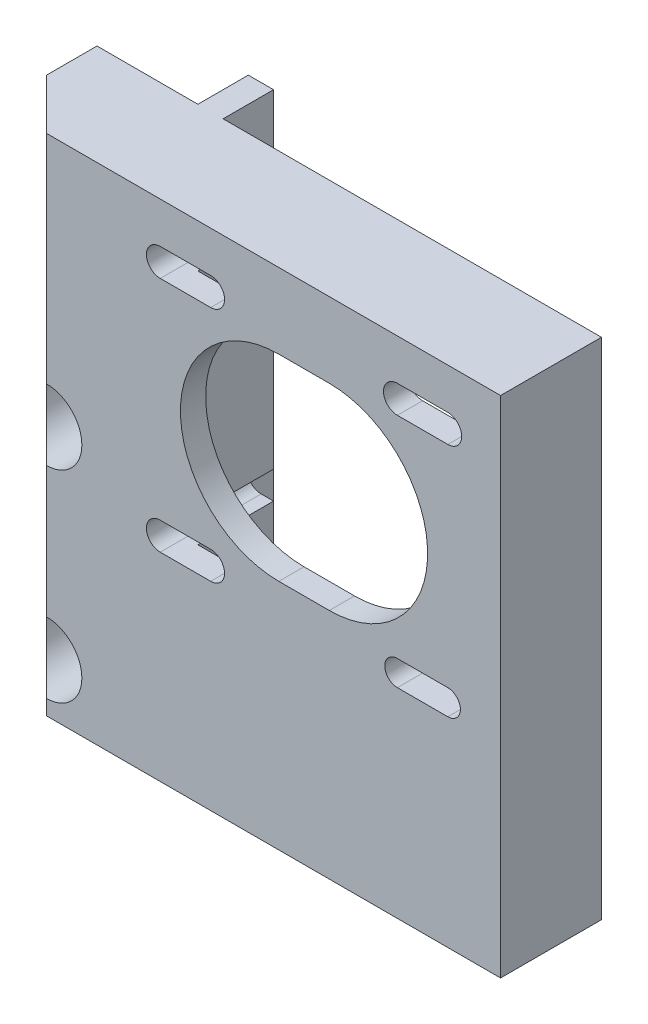
SolidWorks part; units mm, degrees
material "ABS"
ref_plane "Front Plane" through (0, 0, 0) normal (0, 0, 1) x (1, 0, 0)
ref_plane "Top Plane" through (0, 0, 0) normal (0, 1, 0) x (1, 0, 0)
ref_plane "Right Plane" through (0, 0, 0) normal (1, 0, 0) x (0, 0, -1)
sketch "Sketch1" plane through (0, 0, 0) normal (0, 0, 1) x (1, 0, 0)
  line L1 (-57.788, 48.6636) -> (42.212, 48.6636)
  line L2 (-57.788, 48.6636) -> (-57.788, -51.3364)
  line L3 (-57.788, -51.3364) -> (42.212, -51.3364)
  line L4 (42.212, 48.6636) -> (42.212, -51.3364)
  dimension "D1" = 100
  dimension "D2" = 100
extrude "Boss-Extrude1" add sketch "Sketch1" along normal blind 20
sketch "Sketch2" plane through (0, 0, 0) normal (0, 0, -1) x (-1, 0, 0)
  line L0 (-42.212, 48.6636) -> (57.788, 48.6636) construction
  line L1 (37.788, 48.6636) -> (32.788, 48.6636)
  line L2 (37.788, 48.6636) -> (37.788, -51.3364)
  line L3 (37.788, -51.3364) -> (32.788, -51.3364)
  line L4 (32.788, 48.6636) -> (32.788, -51.3364)
  line L5 (57.788, -51.3364) -> (-42.212, -51.3364) construction
  line L6 (57.788, 48.6636) -> (57.788, -51.3364) construction
  dimension "D1" = 20
  dimension "D2" = 5
sketch "Sketch5" plane through (0, 0, 20) normal (0, 0, 1) x (1, 0, 0)
  line L0 (31.7543, -9.2179) -> (21.7543, -9.2179) construction
  line L3 (31.7543, -11.7179) -> (21.7543, -11.7179)
  line L6 (31.7543, -6.7179) -> (21.7543, -6.7179)
  line L9 (8.2543, 14.2821) -> (-1.7457, 14.2821) construction
  line L12 (8.2543, -5.2179) -> (-1.7457, -5.2179)
  line L16 (8.2543, 33.7821) -> (-1.7457, 33.7821)
  line L17 (31.7543, 37.7821) -> (21.7543, 37.7821) construction
  line L18 (31.7543, 35.035) -> (21.7543, 35.035)
  line L19 (31.7543, 40.5292) -> (21.7543, 40.5292)
  line L20 (-15.2457, 37.7821) -> (-25.2457, 37.7821) construction
  line L21 (-15.2457, 35.035) -> (-25.2457, 35.035)
  line L22 (-15.2457, 40.5292) -> (-25.2457, 40.5292)
  line L23 (-15.2457, -9.2179) -> (-25.2457, -9.2179) construction
  line L24 (-15.2457, -11.965) -> (-25.2457, -11.965)
  line L25 (-15.2457, -6.4708) -> (-25.2457, -6.4708)
  arc A12 (31.7543, -11.7179) -> (31.7543, -6.7179) centre (31.7543, -9.2179) ccw
  arc A13 (21.7543, -6.7179) -> (21.7543, -11.7179) centre (21.7543, -9.2179) ccw
  arc A14 (8.2543, -5.2179) -> (8.2543, 33.7821) centre (8.2543, 14.2821) ccw
  arc A15 (-1.7457, 33.7821) -> (-1.7457, -5.2179) centre (-1.7457, 14.2821) ccw
  arc A16 (31.7543, 35.035) -> (31.7543, 40.5292) centre (31.7543, 37.7821) ccw
  arc A17 (21.7543, 40.5292) -> (21.7543, 35.035) centre (21.7543, 37.7821) ccw
  arc A18 (-15.2457, 35.035) -> (-15.2457, 40.5292) centre (-15.2457, 37.7821) ccw
  arc A19 (-25.2457, 40.5292) -> (-25.2457, 35.035) centre (-25.2457, 37.7821) ccw
  arc A20 (-15.2457, -11.965) -> (-15.2457, -6.4708) centre (-15.2457, -9.2179) ccw
  arc A21 (-25.2457, -6.4708) -> (-25.2457, -11.965) centre (-25.2457, -9.2179) ccw
  point P2 (26.7543, -9.2179)
  point P9 (3.2543, 14.2821)
  point P16 (26.7543, 37.7821)
  point P23 (-20.2457, 37.7821)
  point P30 (-20.2457, -9.2179)
  dimension "D5" = 19.5
  dimension "D7" = 2.5
  dimension "D1" = 10
  dimension "D2" = 10
  dimension "D3" = 23.5
  dimension "D4" = 23.5
  dimension "D9" = 47
  dimension "D10" = 23.5
extrude "Cut-Extrude1" cut sketch "Sketch5" against normal blind 20
sketch "Sketch6" plane through (0, 0, 0) normal (0, 0, -1) x (-1, 0, 0)
  line L0 (22.788, 48.6636) -> (-42.212, 48.6636) construction
  line L1 (-37.212, 43.6636) -> (22.788, 43.6636)
  line L2 (-37.212, 43.6636) -> (-37.212, -46.3364)
  line L3 (-37.212, -46.3364) -> (22.788, -46.3364)
  line L4 (22.788, 43.6636) -> (22.788, -46.3364)
  line L5 (-42.212, 43.6636) -> (-42.212, -51.3364) construction
  line L7 (57.788, -51.3364) -> (-42.212, -51.3364) construction
  point P6 (0, 0)
  dimension "D1" = 5
  dimension "D2" = 5
  dimension "D3" = 5
extrude "Cut-Extrude2" cut sketch "Sketch6" against normal blind 15
extrude "Boss-Extrude2" add sketch "Sketch2" along normal blind 10
chamfer "Chamfer1" distance 10 angle 45 1 edges at (-57.788, -1.3364, 20)
sketch "Sketch7" plane through (0, 0, 0) normal (0, 0, -1) x (-1, 0, 0)
  line L0 (57.788, -51.3364) -> (37.788, -51.3364) construction
  line L1 (57.788, 48.6636) -> (57.788, -51.3364) construction
  circle A0 centre (47.788, -41.3364) radius 3
  dimension "D1" = 10
  dimension "D2" = 10
extrude "Cut-Extrude3" cut sketch "Sketch7" against normal blind 50
sketch "Sketch9" plane through (0, 0, 0) normal (0, 0, -1) x (-1, 0, 0)
  circle A0 centre (47.788, -41.3364) radius 7
extrude "Cut-Extrude4" cut sketch "Sketch9" against normal blind 50 from offset 10 offset against normal yes
pattern_linear "LPattern1" count 2 spacing 40 along (0, 1, 0) of "Cut-Extrude3", "Cut-Extrude4"
